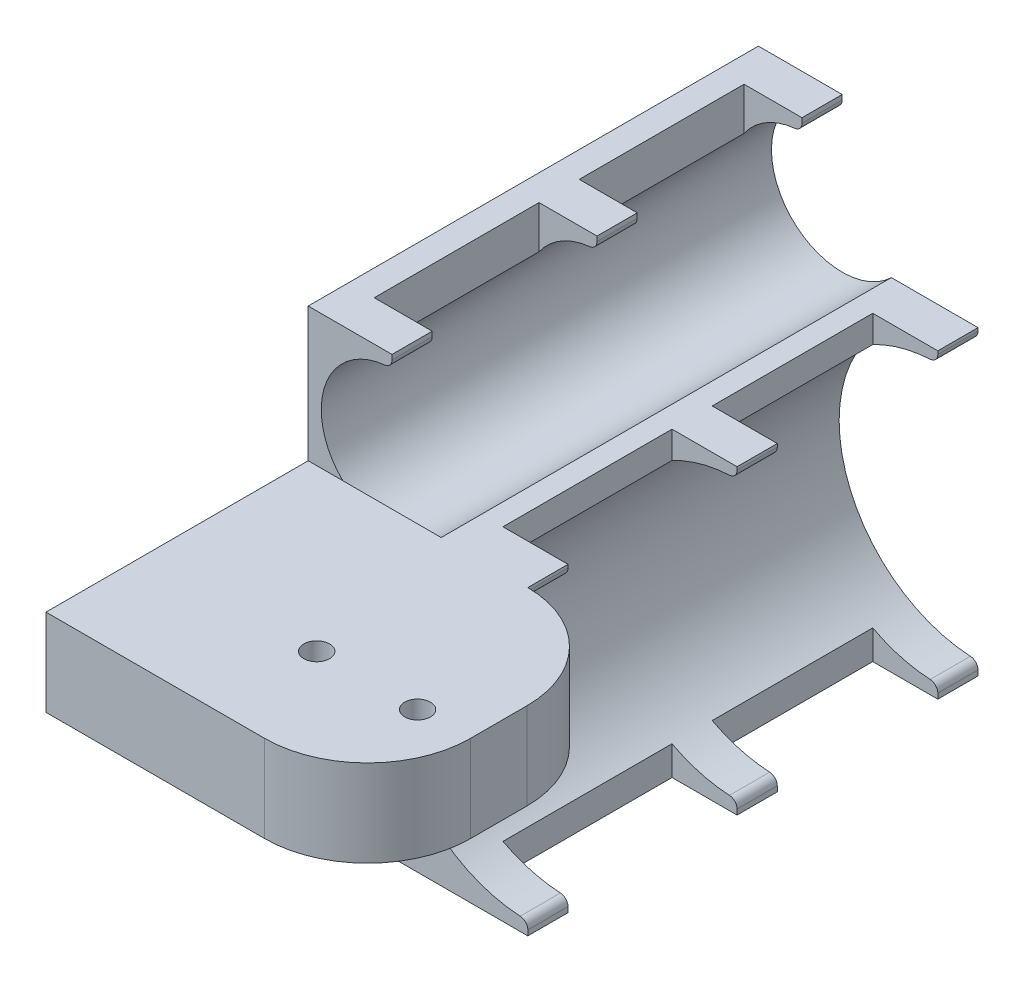
SolidWorks part; units mm, degrees
ref_plane "Front Plane" through (0, 0, 0) normal (0, 0, 1) x (1, 0, 0)
ref_plane "Top Plane" through (0, 0, 0) normal (0, 1, 0) x (1, 0, 0)
ref_plane "Right Plane" through (0, 0, 0) normal (1, 0, 0) x (0, 0, -1)
sketch "Sketch1" plane through (0, 0, 0) normal (0, 0, 1) x (1, 0, 0)
  line L3 (22.4738, 84.758) -> (22.4738, 83.0587)
  line L4 (22.4738, 39.8787) -> (22.4738, 37.8467)
  line L5 (22.4738, 37.8467) -> (-11.6734, 37.8467)
  line L6 (-11.6734, 37.8467) -> (-11.6734, 105.594)
  line L7 (-11.6734, 105.594) -> (1.3586, 105.594)
  line L9 (1.3586, 105.594) -> (1.3586, 103.6651)
  line L10 (22.4738, 84.758) -> (9.0057, 84.758)
  circle A0 centre (1.3586, 92.6651) radius 11 construction
  circle A1 centre (22.4738, 61.4687) radius 21.59 construction
  arc A2 (1.3586, 103.6651) -> (9.0057, 84.758) centre (1.3586, 92.6651) ccw
  arc A3 (22.4738, 83.0587) -> (22.4738, 39.8787) centre (22.4738, 61.4687) ccw
  dimension "D1" = 2.032
extrude "Boss-Extrude1" add sketch "Sketch1" against normal blind 70
sketch "Sketch2" plane through (0, 105.594, 0) normal (0, 1, 0) x (1, 0, 0)
  line L0 (22.4738, 70) -> (22.4738, 0) construction
  line L1 (-7.6541, 63.75) -> (22.4738, 63.75)
  line L2 (-7.6541, 63.75) -> (-7.6541, 38.125)
  line L3 (-7.6541, 6.25) -> (22.4738, 6.25)
  line L4 (22.4738, 63.75) -> (22.4738, 38.125)
  line L5 (-7.6541, 38.125) -> (22.4738, 38.125)
  line L7 (22.4738, 31.875) -> (-7.6541, 31.875)
  line L8 (22.4738, 31.875) -> (22.4738, 6.25)
  line L9 (-7.6541, 31.875) -> (-7.6541, 6.25)
  line L10 (9.0057, 70) -> (-9.6414, 70) construction
  line L11 (-9.6414, 0) -> (9.0057, 0) construction
  dimension "D1" = 6.25
  dimension "D2" = 6.25
  dimension "D3" = 6.25
extrude "Cut-Extrude1" cut sketch "Sketch2" against normal blind 10
sketch "Sketch3" plane through (0, 84.758, 0) normal (0, 1, 0) x (1, 0, 0)
  line L0 (12.3586, 0.5606) -> (12.3586, 68.5606) construction
  line L5 (12.3586, 63.75) -> (48.4941, 63.75)
  line L6 (12.3586, 63.75) -> (12.3586, 38.7891)
  line L7 (12.3586, 6.25) -> (48.4941, 6.25)
  line L8 (48.4941, 63.75) -> (48.4941, 38.7891)
  line L9 (22.4738, 0) -> (9.0057, 0) construction
  line L10 (22.4738, 70) -> (9.0057, 70) construction
  line L11 (12.3586, 38.7891) -> (48.4941, 38.7891)
  line L13 (48.4941, 32.5391) -> (12.3586, 32.5391)
  line L14 (12.3586, 32.5391) -> (12.3586, 6.25)
  line L15 (48.4941, 32.5391) -> (48.4941, 6.25)
  point P14 (15.7398, 70)
  dimension "D1" = 6.25
  dimension "D2" = 6.25
  dimension "D3" = 6.25
extrude "Cut-Extrude2" cut sketch "Sketch3" against normal through all
sketch "Sketch5" plane through (-11.6734, 0, 0) normal (-1, 0, 0) x (0, 0, 1)
  line L0 (40.7692, 62.2625) -> (40.7692, 81.4327) construction
  line L1 (0, 84.758) -> (40.7692, 84.758)
  line L2 (0, 84.758) -> (0, 71.258)
  line L3 (0, 71.258) -> (40.7692, 71.258)
  line L4 (40.7692, 84.758) -> (40.7692, 71.258)
  dimension "D1" = 13.5
extrude "Boss-Extrude2" add sketch "Sketch5" against normal blind 50
sketch "Sketch6" plane through (0, 84.758, 0) normal (0, 1, 0) x (1, 0, 0)
  circle A0 centre (14.6476, -25) radius 2
  circle A1 centre (30.3294, -25) radius 2
  dimension "D1" = 4
  dimension "D2" = 4
extrude "Cut-Extrude3" cut sketch "Sketch6" against normal blind 50
fillet "Fillet1" radius 1.25 9 edges at (22.4738, 39.8787, -66.875) (22.4738, 39.8787, -35.6641) (22.4738, 39.8787, -3.125) (22.4738, 83.0587, -3.125) (22.4738, 83.0587, -35.6641) (22.4738, 83.0587, -66.875) (1.3586, 103.6651, -66.875) (1.3586, 103.6651, -35) (1.3586, 103.6651, -3.125)
fillet "Fillet2" radius 16 2 edges at (38.3266, 78.008, 0) (38.3266, 78.008, 40.7692)
